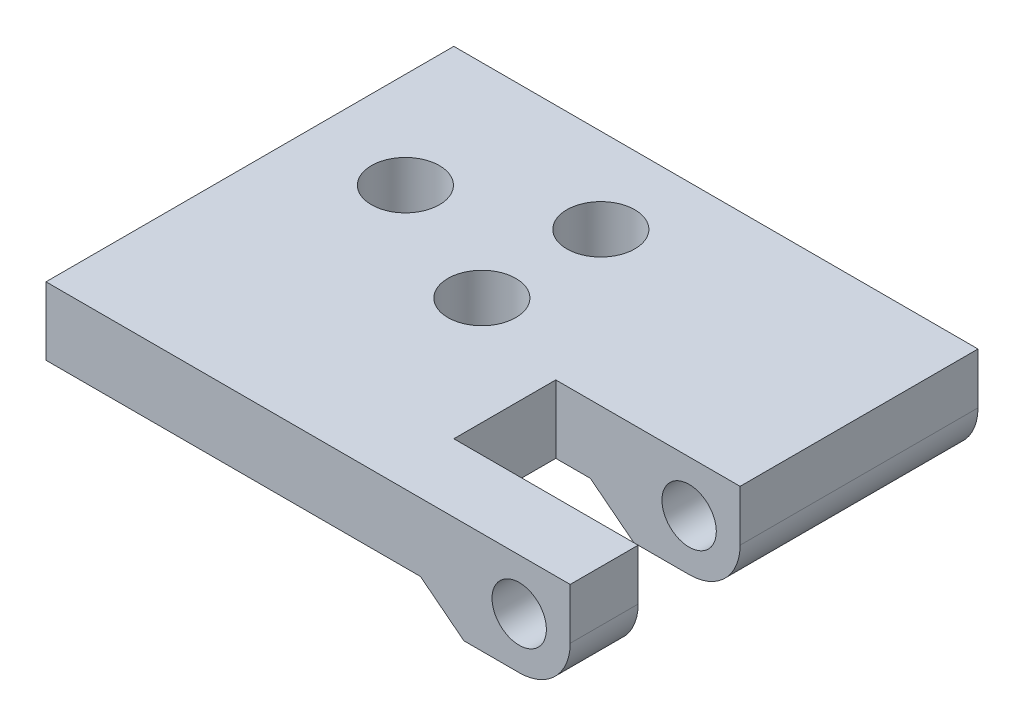
SolidWorks part; units mm, degrees
ref_plane "前视基准面" through (0, 0, 0) normal (0, 0, 1) x (1, 0, 0)
ref_plane "上视基准面" through (0, 0, 0) normal (0, 1, 0) x (1, 0, 0)
ref_plane "右视基准面" through (0, 0, 0) normal (1, 0, 0) x (0, 0, -1)
sketch "草图1" plane through (0, 0, 0) normal (0, 1, 0) x (1, 0, 0)
  line L0 (-12.0433, 4.7008) -> (-12.0433, -2.2992) construction
  line L1 (-25.6944, 9.7008) -> (4.3056, 9.7008)
  line L2 (-25.6944, 9.7008) -> (-25.6944, -14.2992)
  line L3 (-25.6944, -14.2992) -> (4.3056, -14.2992)
  line L4 (4.3056, 9.7008) -> (4.3056, -14.2992)
  line L5 (4.3056, -10.2992) -> (-5.6944, -10.2992)
  line L6 (4.3056, -10.2992) -> (4.3056, -4.2992)
  line L7 (4.3056, -4.2992) -> (-5.6944, -4.2992)
  line L8 (-5.6944, -10.2992) -> (-5.6944, -4.2992)
  circle A0 centre (-20.0433, 1.2008) radius 2
  circle A1 centre (-12.0433, 4.7008) radius 2
  circle A2 centre (-12.0433, -2.2992) radius 2
  point P10 (-12.0433, 1.2008)
  dimension "D7" = 8
  dimension "D8" = 7
  dimension "D1" = 20
  dimension "D2" = 20
  dimension "D3" = 6
  dimension "D4" = 10
  dimension "D5" = 4
  dimension "D6" = 8.5
extrude "凸台-拉伸2" add sketch "草图1" along normal blind 6
sketch "草图2" plane through (0, 0, 14.2992) normal (0, 0, 1) x (1, 0, 0)
  line L0 (4.3056, 0) -> (0, 6) construction
  line L1 (-25.6944, 6) -> (4.3056, 6) construction
  circle A0 centre (2.1528, 3) radius 1.6
  point P5 (2.1528, 3)
extrude "切除-拉伸2" cut sketch "草图2" against normal blind 26
sketch "草图3" plane through (0, 0, 0) normal (0, -1, 0) x (1, 0, 0)
  line L0 (-25.6944, -9.7008) -> (4.3056, -9.7008) construction
  line L1 (-25.6944, 14.2992) -> (-3.6581, 14.2992)
  line L2 (-25.6944, 14.2992) -> (-25.6944, -9.7008)
  line L3 (-25.6944, -9.7008) -> (-3.6581, -9.7008)
  line L4 (-3.6581, 14.2992) -> (-3.6581, -9.7008)
extrude "切除-拉伸3" cut sketch "草图3" against normal blind 2
sketch "草图4" plane through (0, 0, 14.2992) normal (0, 0, 1) x (1, 0, 0)
  line L0 (-3.6581, 2) -> (-1.1001, 0)
  line L1 (-1.1001, 0) -> (-3.6581, 0)
  line L2 (-3.6581, 0) -> (-3.6581, 2)
  line L3 (-1.1001, 0) -> (-0.8205, 0)
  line L4 (-3.6581, 0) -> (4.3056, 0) construction
  line M6 (-3.6581, 2) -> (-3.6581, 0)
  line M7 (-3.6581, 0) -> (4.3056, 0)
extrude "切除-拉伸4" cut sketch "草图4" against normal blind 27 contours L0 M6 M7
sketch "草图5" plane through (0, 0, -9.7008) normal (0, 0, -1) x (-1, 0, 0)
  line L0 (25.6944, 6) -> (-4.3056, 6) construction
  line L1 (-4.3056, 6) -> (-4.3056, 0) construction
  line L4 (-2.1528, 0) -> (-4.3056, 0)
  line L5 (-4.3056, 0) -> (-4.3056, 0.9106)
  circle A0 centre (-2.1528, 3) radius 3 construction
  arc A2 (-2.1528, 0) -> (-4.3056, 0.9106) centre (-2.1528, 3) cw
  point P16 (0, 0)
  point P17 (0, 0)
  point P18 (0, 0)
extrude "切除-拉伸7" cut sketch "草图5" against normal blind 24
sketch "草图8" plane through (0, 0, -9.7008) normal (0, 0, -1) x (-1, 0, 0)
  line L0 (-4.3056, 6) -> (-5.1528, 6)
  line L1 (-5.1528, 6) -> (-5.1528, 3)
  line L2 (-4.3056, 6) -> (-4.3056, 5.0894)
  line L3 (-4.3056, 6) -> (-4.3056, 0.9106) construction
  line L4 (-4.3056, 5.0894) -> (-4.3056, 0.9106)
  circle A1 centre (-2.1528, 3) radius 3 construction
  arc A2 (-4.3056, 0.9106) -> (-5.1528, 3) centre (-2.1528, 3) cw
  line M8 (-4.3056, 6) -> (-4.3056, 0.9106)
extrude "凸台-拉伸4" add sketch "草图8" against normal blind 24 contours A2 L0 L1 M8
sketch "草图9" plane through (4.3056, 0, 0) normal (-1, 0, 0) x (0, 0, 1)
  line L1 (10.2992, 6) -> (4.2992, 6)
  line L2 (10.2992, 6) -> (10.2992, 0.9106)
  line L3 (10.2992, 0.9106) -> (4.2992, 0.9106)
  line L4 (4.2992, 6) -> (4.2992, 0.9106)
extrude "切除-拉伸8" cut sketch "草图9" against normal blind 24
